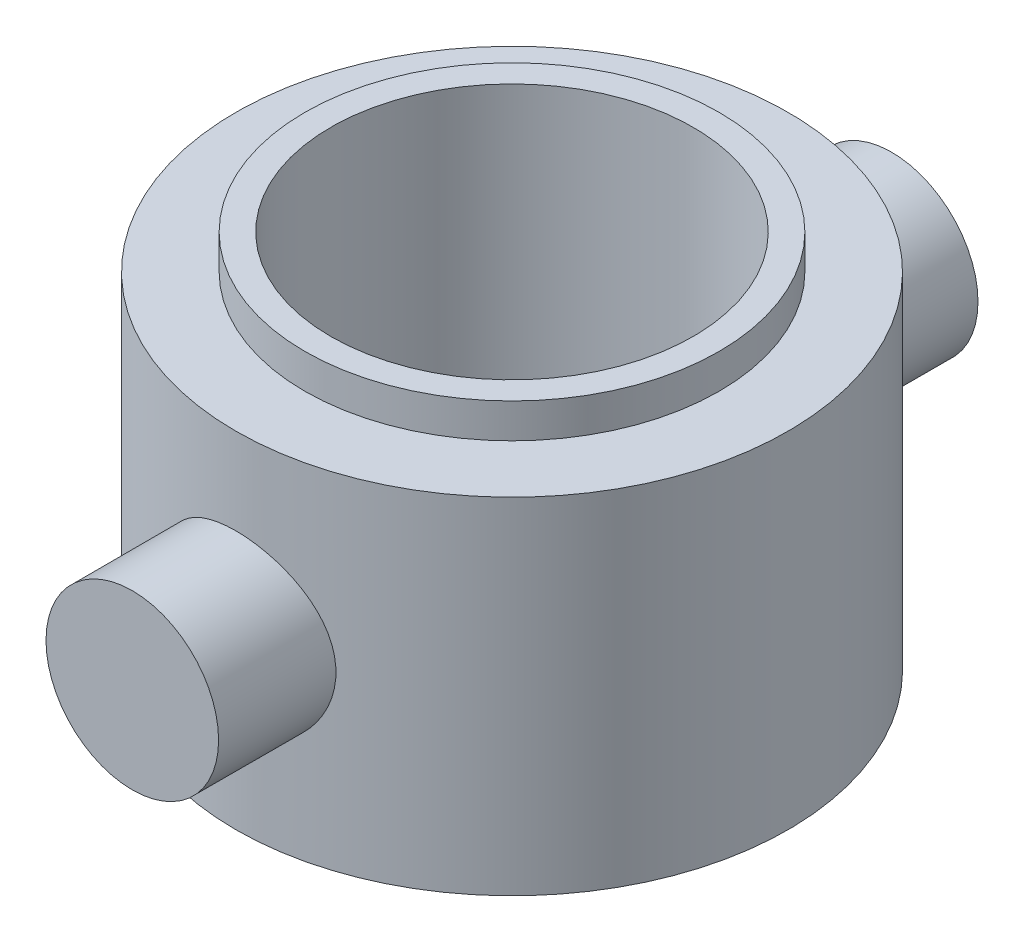
SolidWorks part; units mm, degrees
ref_plane "Front Plane" through (0, 0, 0) normal (0, 0, 1) x (1, 0, 0)
ref_plane "Top Plane" through (0, 0, 0) normal (0, 1, 0) x (1, 0, 0)
ref_plane "Right Plane" through (0, 0, 0) normal (1, 0, 0) x (0, 0, -1)
sketch "Sketch1" plane through (0, 0, 0) normal (0, 1, 0) x (1, 0, 0)
  circle A0 centre (0, 0) radius 5.25
  circle A1 centre (0, 0) radius 8
  dimension "D1" = 10.5
  dimension "D2" = 16
extrude "Boss-Extrude1" add sketch "Sketch1" along normal mid plane 10
sketch "Sketch2" plane through (0, 5, 0) normal (0, 1, 0) x (1, 0, 0)
  circle A0 centre (0, 0) radius 5.25
  circle A1 centre (0, 0) radius 6
  circle A3 centre (0, 0) radius 5.25 construction
  dimension "D1" = 12
extrude "Boss-Extrude2" add sketch "Sketch2" along normal mid plane 2
ref_plane "Plane1" through (0, 0, 6) normal (0, 0, 1) x (1, 0, 0)
sketch "Sketch3" plane through (0, 0, 6) normal (0, 0, 1) x (1, 0, 0)
  circle A0 centre (0, 0) radius 2.5
  dimension "D1" = 5
extrude "Boss-Extrude3" add sketch "Sketch3" along normal blind 5
mirror "Mirror1" about plane through (0, 0, 0) normal (0, 0, 1) of "Boss-Extrude3"
